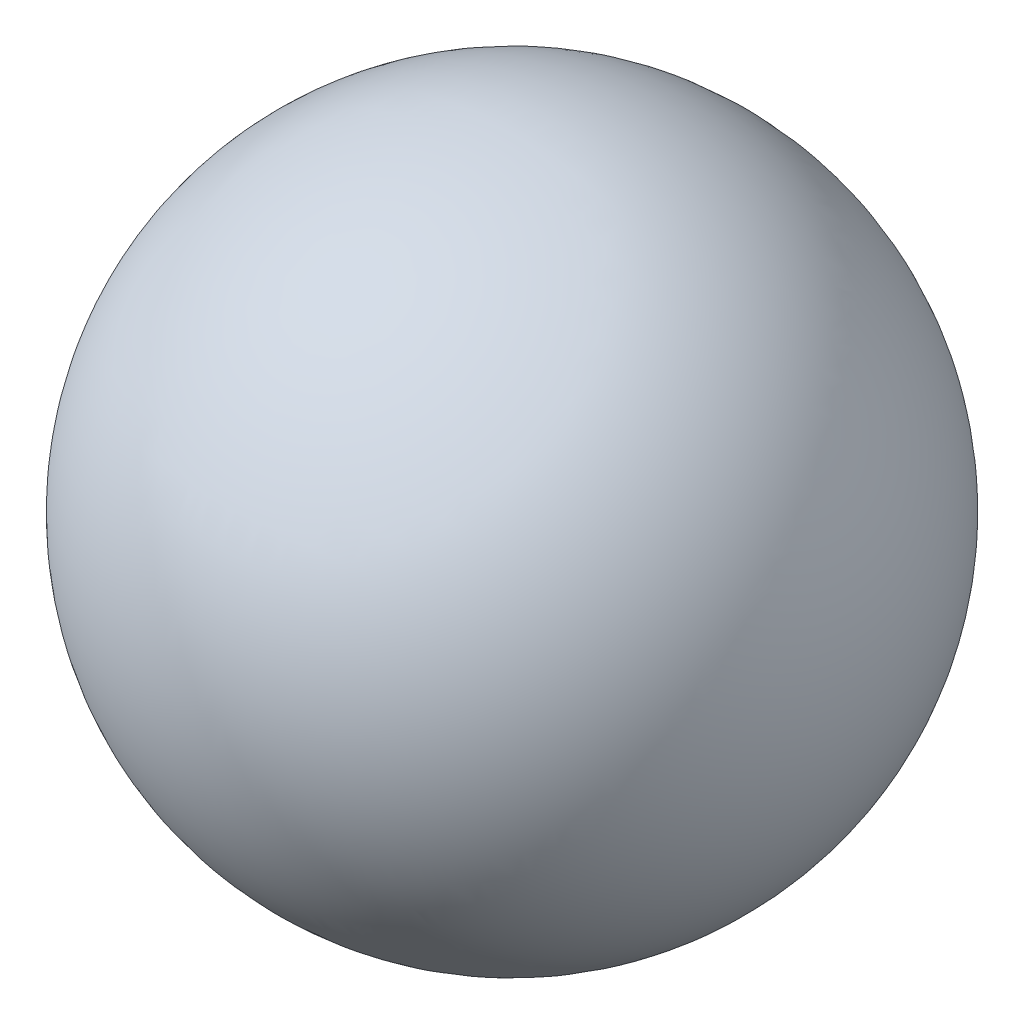
SolidWorks part; units mm, degrees
ref_plane "Plano frontal" through (0, 0, 0) normal (0, 0, 1) x (1, 0, 0)
ref_plane "Plano superior" through (0, 0, 0) normal (0, 1, 0) x (1, 0, 0)
ref_plane "Plano direito" through (0, 0, 0) normal (1, 0, 0) x (0, 0, -1)
sketch "Esboço1" plane through (0, 0, 0) normal (0, 0, 1) x (1, 0, 0)
  line L0 (-75, -27.075) -> (75, -27.075) construction
  line L1 (-59.4398, -27.05) -> (-46.4651, -27.075) construction
  line L2 (-52.2917, -27.05) -> (-60.2917, -27.05) construction
  line L3 (-49.5, -27.0692) -> (-57.4999, -27.0538)
  arc A0 (-57.4999, -27.0538) -> (-49.5, -27.0692) centre (-53.5, -27.075) ccw
  dimension "D1" = 8
revolve "Revolução1" add sketch "Esboço1" angle 360 about L1
